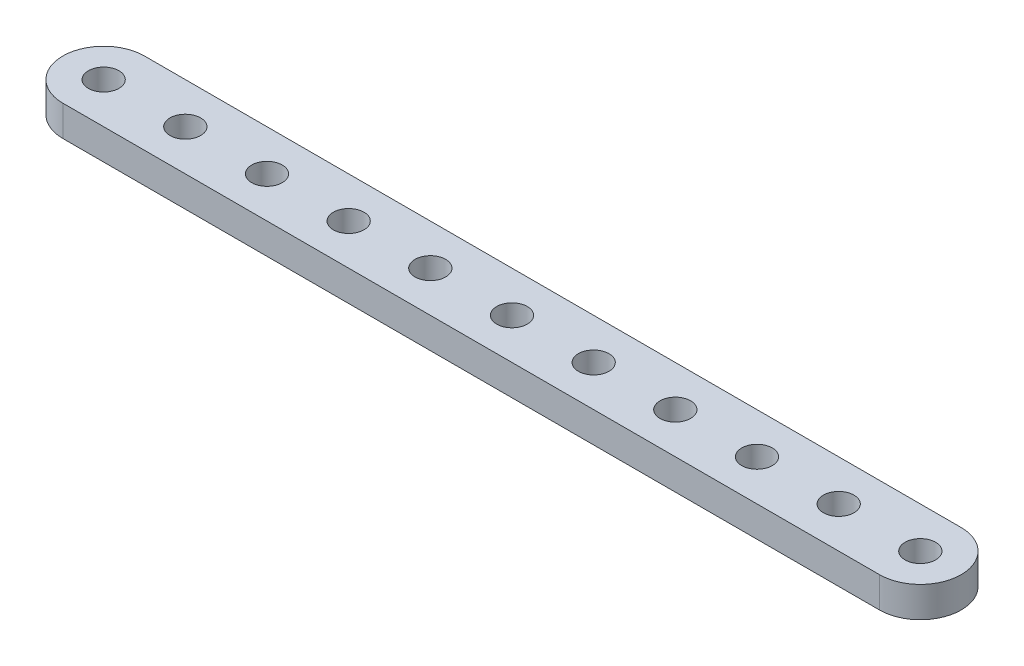
SolidWorks part; units mm, degrees
ref_plane "Front Plane" through (0, 0, 0) normal (0, 0, 1) x (1, 0, 0)
ref_plane "Top Plane" through (0, 0, 0) normal (0, 1, 0) x (1, 0, 0)
ref_plane "Right Plane" through (0, 0, 0) normal (1, 0, 0) x (0, 0, -1)
sketch "Sketch2" plane through (0, 0, 0) normal (0, 1, 0) x (1, 0, 0)
  line L0 (0, 0) -> (80, 0) construction
  line L1 (0, 4) -> (80, 4)
  line L2 (0, -4) -> (80, -4)
  arc A0 (0, 4) -> (0, -4) centre (0, 0) ccw
  arc A1 (80, -4) -> (80, 4) centre (80, 0) ccw
  circle A2 centre (0, 0) radius 1.5
  circle A3 centre (8, 0) radius 1.5
  circle A4 centre (16, 0) radius 1.5
  circle A5 centre (24, 0) radius 1.5
  circle A6 centre (32, 0) radius 1.5
  circle A7 centre (40, 0) radius 1.5
  circle A8 centre (48, 0) radius 1.5
  circle A9 centre (56, 0) radius 1.5
  circle A10 centre (64, 0) radius 1.5
  circle A11 centre (72, 0) radius 1.5
  circle A12 centre (80, 0) radius 1.5
  point P3 (40, 0)
  dimension "D1" = 3
  dimension "D2" = 8
  dimension "D3" = 80
extrude "Boss-Extrude2" add sketch "Sketch2" along normal blind 3
